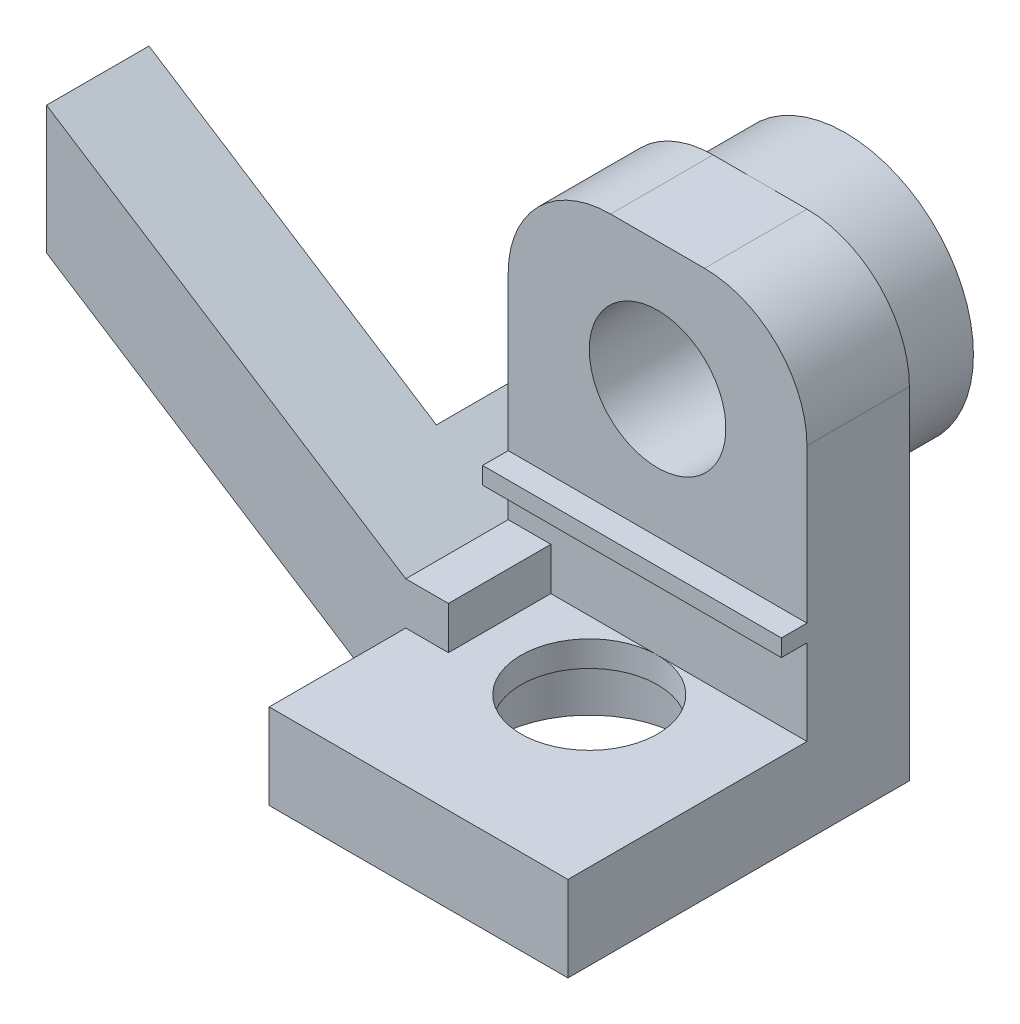
SolidWorks part; units mm, degrees
ref_plane "Front Plane" through (0, 0, 0) normal (0, 0, 1) x (1, 0, 0)
ref_plane "Top Plane" through (0, 0, 0) normal (0, 1, 0) x (1, 0, 0)
ref_plane "Right Plane" through (0, 0, 0) normal (1, 0, 0) x (0, 0, -1)
sketch "Sketch1" plane through (0, 0, 0) normal (0, 1, 0) x (1, 0, 0)
  line L1 (-17.5, 6) -> (17.5, 6)
  line L2 (-17.5, 6) -> (-17.5, -6)
  line L3 (-17.5, -6) -> (17.5, -6)
  line L4 (17.5, 6) -> (17.5, -6)
  line L5 (-17.5, 6) -> (17.5, -6) construction
  line L6 (-17.5, -6) -> (17.5, 6) construction
  point P0 (0, 0)
extrude "Boss-Extrude1" add sketch "Sketch1" along normal blind 20
sketch "Sketch2" plane through (0, 20, 0) normal (0, 1, 0) x (1, 0, 0)
  line L0 (17.5, -6) -> (17.5, 6) construction
  line L1 (-17.5, 6) -> (17.5, 6)
  line L2 (-17.5, 6) -> (-17.5, -6)
  line L3 (-17.5, -6) -> (17.5, -6)
  line L4 (17.5, 6) -> (17.5, -6)
  line L5 (-17.5, -6) -> (17.5, -6) construction
extrude "Boss-Extrude2" add sketch "Sketch2" along normal blind 10
sketch "Sketch4" plane through (0, 0, -6) normal (0, 0, -1) x (-1, 0, 0)
  line L0 (-17.5, 0) -> (-17.5, 15)
  line L1 (-17.5, 30) -> (-17.5, 0) construction
  line L2 (-17.5, 15) -> (17.5, 15)
  line L3 (17.5, 30) -> (17.5, 0) construction
  circle A0 centre (0, 15) radius 8
extrude "Cut-Extrude1" cut sketch "Sketch4" against normal blind 12 contours L2 A0 | L2 A0
fillet "Fillet1" radius 12 2 edges at (-17.5, 30, 0) (17.5, 30, 0)
sketch "Sketch5" plane through (0, 0, -6) normal (0, 0, -1) x (-1, 0, 0)
  circle A0 centre (0, 15) radius 12
  circle A1 centre (0, 15) radius 15
extrude "Boss-Extrude3" add sketch "Sketch5" along normal blind 10
sketch "Sketch6" plane through (0, 0, 0) normal (0, -1, 0) x (1, 0, 0)
  line L1 (-17.5, -6) -> (17.5, -6)
  line L2 (-17.5, -6) -> (-17.5, 9)
  line L3 (-17.5, 9) -> (17.5, 9)
  line L4 (17.5, -6) -> (17.5, 9)
extrude "Boss-Extrude4" add sketch "Sketch6" along normal blind 2
sketch "Sketch7" plane through (0, -2, 0) normal (0, -1, 0) x (1, 0, 0)
  line L1 (-17.5, -6) -> (17.5, -6)
  line L2 (-17.5, -6) -> (-17.5, 6)
  line L3 (-17.5, 6) -> (17.5, 6)
  line L4 (17.5, -6) -> (17.5, 6)
extrude "Boss-Extrude5" add sketch "Sketch7" along normal blind 10
sketch "Sketch8" plane through (0, -12, 0) normal (0, -1, 0) x (1, 0, 0)
  line L5 (-17.5, -6) -> (17.5, -6)
  line L6 (-17.5, -6) -> (-17.5, 34)
  line L7 (-17.5, 34) -> (17.5, 34)
  line L8 (17.5, -6) -> (17.5, 34)
extrude "Boss-Extrude6" add sketch "Sketch8" along normal blind 10
sketch "Sketch10" plane through (0, -22, 0) normal (0, -1, 0) x (1, 0, 0)
  circle A0 centre (0, 14) radius 11.2
extrude "Cut-Extrude2" cut sketch "Sketch10" against normal blind 7
sketch "Sketch11" plane through (0, -15, 0) normal (0, -1, 0) x (1, 0, 0)
  circle A0 centre (0, 14) radius 8
extrude "Cut-Extrude3" cut sketch "Sketch11" against normal blind 3
sketch "Sketch12" plane through (0, 0, -6) normal (0, 0, -1) x (-1, 0, 0)
  line L5 (17.5, -22) -> (17.5, -7)
  line L6 (17.5, 18) -> (17.5, -22) construction
  line L7 (17.5, -7) -> (25.9151, -1.5976)
  line L8 (25.9151, -1.5976) -> (25.9151, -16.5976)
  line L9 (25.9151, -16.5976) -> (17.5, -22)
extrude "Boss-Extrude7" add sketch "Sketch12" against normal blind 12
sketch "Sketch13" plane through (0, 0, 6) normal (0, 0, 1) x (1, 0, 0)
  line L0 (-17.5, -22) -> (-17.5, -7)
  line L1 (-17.5, -7) -> (-59.5755, 20.012)
  line L2 (-25.9151, -1.5976) -> (-17.5, -7) construction
  line L3 (-17.5, -22) -> (-59.5755, 5.012)
  line L4 (-17.5, -22) -> (-25.9151, -16.5976) construction
  line L5 (-59.5755, 5.012) -> (-59.5755, 20.012)
extrude "Boss-Extrude8" add sketch "Sketch13" along normal blind 12
sketch "Sketch14" plane through (-17.5, 0, 0) normal (1, 0, 0) x (0, 0, -1)
  line L1 (-18, -7) -> (-6, -7)
  line L2 (-18, -7) -> (-18, -12)
  line L3 (-18, -12) -> (-6, -12)
  line L4 (-6, -7) -> (-6, -12)
extrude "Boss-Extrude9" add sketch "Sketch14" along normal blind 5
